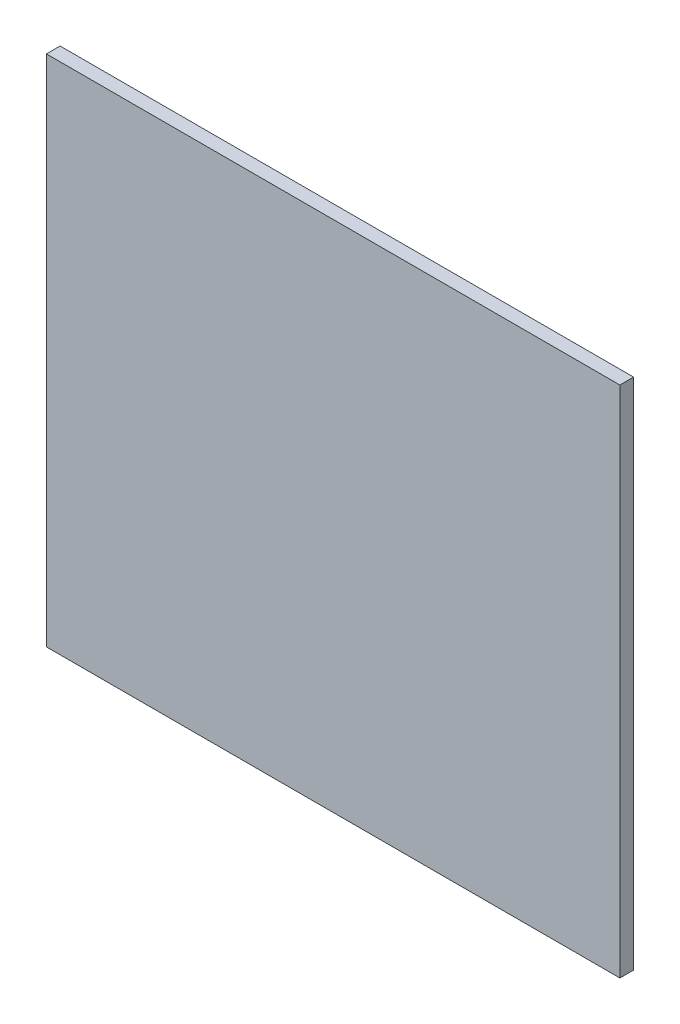
SolidWorks part; units mm, degrees
ref_plane "Front Plane" through (0, 0, 0) normal (0, 0, 1) x (1, 0, 0)
ref_plane "Top Plane" through (0, 0, 0) normal (0, 1, 0) x (1, 0, 0)
ref_plane "Right Plane" through (0, 0, 0) normal (1, 0, 0) x (0, 0, -1)
sketch "Sketch1" plane through (0, 0, 0) normal (0, 0, 1) x (1, 0, 0)
  line L1 (-106.3625, 95.25) -> (106.3625, 95.25)
  line L2 (-106.3625, 95.25) -> (-106.3625, -95.25)
  line L3 (-106.3625, -95.25) -> (106.3625, -95.25)
  line L4 (106.3625, 95.25) -> (106.3625, -95.25)
  line L5 (-106.3625, 95.25) -> (106.3625, -95.25) construction
  line L6 (-106.3625, -95.25) -> (106.3625, 95.25) construction
  point P0 (0, 0)
  dimension "D1" = 212.725
  dimension "D2" = 190.5
extrude "Boss-Extrude1" add sketch "Sketch1" along normal blind 5.08
